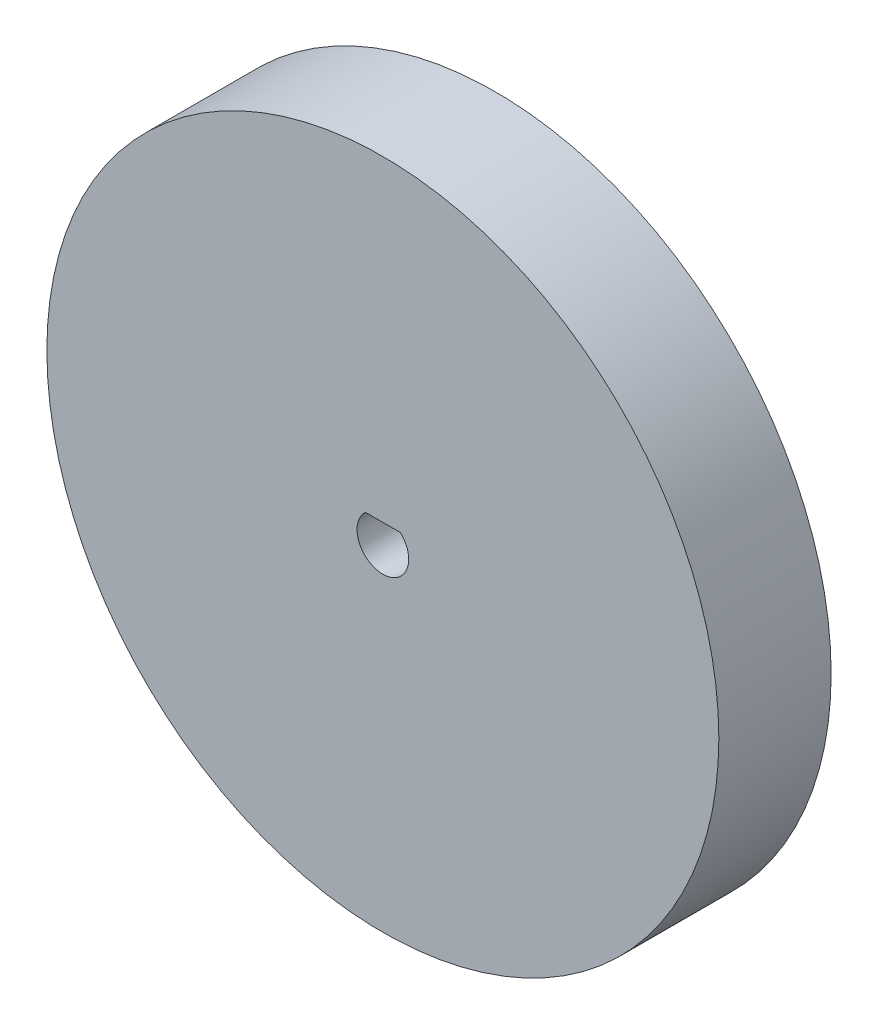
SolidWorks part; units mm, degrees
ref_plane "Front Plane" through (0, 0, 0) normal (0, 0, 1) x (1, 0, 0)
ref_plane "Top Plane" through (0, 0, 0) normal (0, 1, 0) x (1, 0, 0)
ref_plane "Right Plane" through (0, 0, 0) normal (1, 0, 0) x (0, 0, -1)
sketch "Sketch1" plane through (0, 0, 0) normal (0, 0, 1) x (1, 0, 0)
  circle A0 centre (0, 0) radius 38
  dimension "D1" = 76
extrude "Boss-Extrude1" add sketch "Sketch1" along normal blind 12.7
sketch "Sketch2" plane through (0, 0, 12.7) normal (0, 0, 1) x (1, 0, 0)
  line L1 (1.9675, 2.159) -> (-1.9675, 2.159)
  line L2 (1.9675, 2.159) -> (1.9675, 2.921) construction
  line L3 (1.9675, 2.921) -> (-1.9675, 2.921) construction
  line L4 (-1.9675, 2.159) -> (-1.9675, 2.921) construction
  circle A0 centre (0, 0) radius 2.921 construction
  arc A1 (1.9675, 2.159) -> (-1.9675, 2.159) centre (0, 0) cw
  dimension "D1" = 5.842
  dimension "D2" = 0.762
extrude "Cut-Extrude1" cut sketch "Sketch2" against normal through all
equation "\"FoamCore\" = \".2\""
equation "\"MDF\" = \".2\""
equation "\"GMaterial\"= \".2\""
equation "\"PVCMountDiameter\" = \"0.5in\""
equation "\"PVCMountDistanceToEdge\" = \"0.5\""
equation "\"PVCThickness\" = \"0.13in\""
equation "\"BaseWidth\" = \"8in\""
equation "\"BaseLength\" = \"10in\""
equation "\"BallDiameter\" = \"38mm\""
equation "\"BaseGap\" = \"4in\""
equation "\"FunnelTopDiameter\" = \"8in\""
equation "\"FunnelTopDepth\" = \"0.5in\""
equation "\"BallGap\" = \"0.1in\""
equation "\"FunnelLength\" = 3in"
equation "\"FunnelMaterial\" = 0.1in"
equation "\"FunnelLowerDiameter\" = 1.9in"
equation "\"FunnelDepth\" = 1.5in"
equation "\"FunnelBendLength\" = 2*pi*\"FunnelLowerDiameter\"/2*135"
equation "\"AmmoFeederLength\" = 1.5in + 76mm"
equation "\"AmmoFeederCutoffLength\"= \"MovingWheelDiameter\""
equation "\"WheelThickness\" = 0.5in"
equation "\"LauncherWheelDiameter\" = 76mm"
equation "\"MotorFrontLength\" = 0.95in"
equation "\"MotorBodyTotalLength\" = 2.03in"
equation "\"MotorFrontDiameter\" = 1.5in"
equation "\"MotorLowerDriveshaftDiameter\" = 0.46in"
equation "\"MotorLowerDriveshaftThickness\" = 0.25in"
equation "\"MotorFullDriveshaftLength\" = 0.78in"
equation "\"MotorDriveshaftDiameter\" = 0.23in"
equation "\"MotorDriveshaftFlatThickness\" = 0.2in"
equation "\"MotorRearDiameter\" = 31.9mm"
equation "\"MotorDriveshaftBottomToTop\" = 31.1mm"
equation "\"MotorFlatDriveshaftLength\" = 11.7mm"
equation "\"MotorDistanceBetweenLowerandTopHoles\" = 0.5in"
equation "\"MotorMountsDistanceFromEdge\" = 0.06in"
equation "\"MotorScrewMountDiameter\" = 0.1in"
equation "\"MotorScrewMountDepth\" = 0.13in"
equation "\"HBRidgeScrewHoleDeep\" = 0.18in"
equation "\"MotorMountWidth\" = \"1.61in\""
equation "\"MotorMountLength\" = \"1.58in\""
equation "\"MotorMountToEdgeGap\" = \"3.3mm\""
equation "\"MotorMountToInsideEdgeGap\" = \"6.5mm\""
equation "\"MotorMountToMountWidthGap\" = \"25.8mm\""
equation "\"MotorMountToMountLengthGap\" = \"20.5mm\""
equation "\"MotorMountMaterialThickness\" = 1.6mm"
equation "\"MotorMountBaseScrewholeDiameter\" = 3.8mm"
equation "\"MotorMountBaseDistancebetweenHoles\" = 0.8in"
equation "\"MotorMountHeight\" = 1.85in"
equation "\"HBridgeWidth\" = 2.25in"
equation "\"HBridgeLength\" = 1.40in"
equation "\"UnoWidth\" = 3.13in"
equation "\"UnoLength\" = 3.06in"
equation "\"BatteryWidth\" = 1.15in"
equation "\"BatteryLength\" = 3.86in"
equation "\"ScrewDiameter\" = 2.7mm"
equation "\"MotorMountFaceScrewtoBase\" = 0.46in"
equation "\"MotorMountFaceDistanceBetweenScrews\" = 0.95in"
equation "\"MotorMountFaceMiddletoEdge\" = 0.16in"
equation "\"MotorMountFaceBottomtoEdge\" = 0.42in"
equation "\"MotorMountCenterholeHeight\" = 1.04in"
equation "\"MotorMountCenterholetoEdge\" = 0.25in"
equation "\"MovingWheelDiameter\" = 76mm"
equation "\"MovingWheelThickness\" = 0.5in"
equation "\"D1@Sketch1\"=\"MovingWheelDiameter\""
equation "\"D1@Boss-Extrude1\"=\"MovingWheelDiameter\""
equation "\"D1@Sketch2\"=\"MotorDriveshaftDiameter\""
equation "\"D2@Sketch2\"=\"MotorDriveshaftDiameter\"-\"MotorDriveshaftFlatThickness\""
